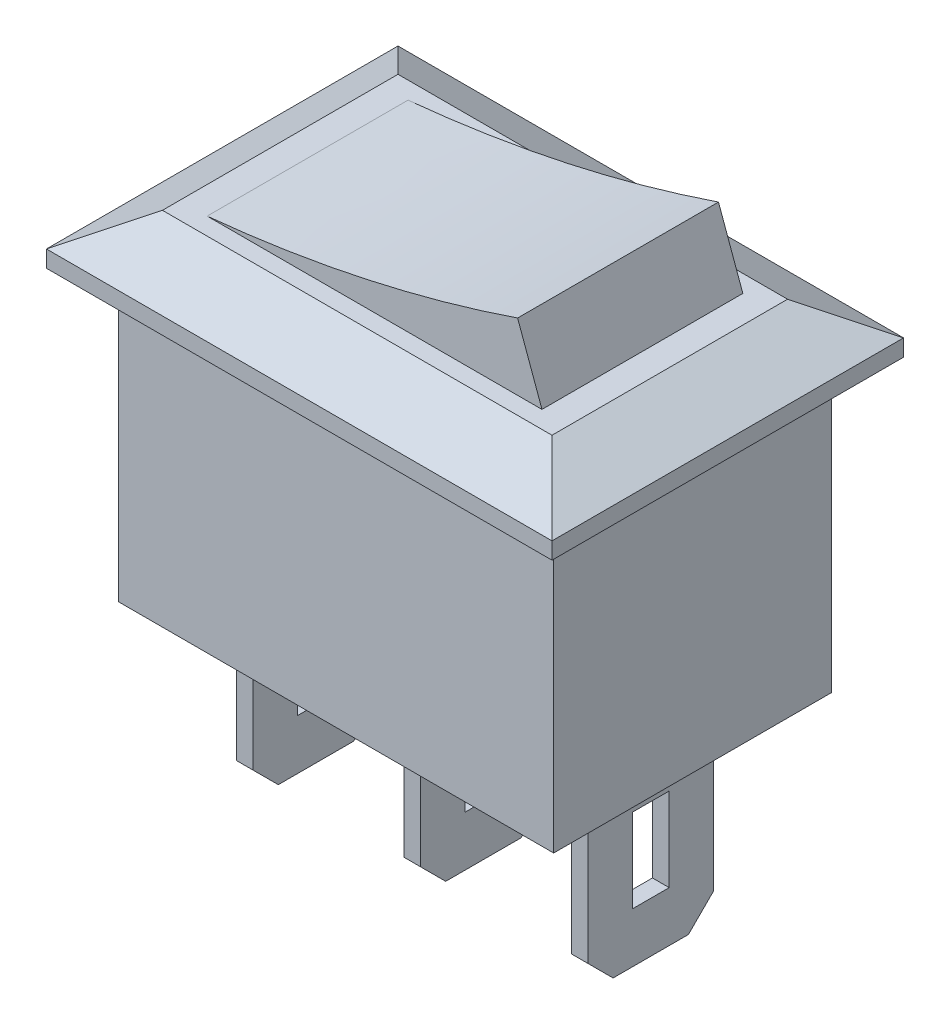
SolidWorks part; units mm, degrees
material "Custom Plastic"
ref_plane "Front Plane" through (0, 0, 0) normal (0, 0, 1) x (1, 0, 0)
ref_plane "Top Plane" through (0, 0, 0) normal (0, 1, 0) x (1, 0, 0)
ref_plane "Right Plane" through (0, 0, 0) normal (1, 0, 0) x (0, 0, -1)
sketch "Sketch1" plane through (0, 0, 0) normal (0, 1, 0) x (1, 0, 0)
  line L1 (6.5, -4.15) -> (-6.5, -4.15)
  line L2 (6.5, -4.15) -> (6.5, 4.15)
  line L3 (6.5, 4.15) -> (-6.5, 4.15)
  line L4 (-6.5, -4.15) -> (-6.5, 4.15)
  line L5 (6.5, -4.15) -> (-6.5, 4.15) construction
  line L6 (6.5, 4.15) -> (-6.5, -4.15) construction
  point P0 (0, 0)
  dimension "D1" = 8.3
  dimension "D2" = 13
extrude "Boss-Extrude1" add sketch "Sketch1" along normal blind 8.65
sketch "Sketch3" plane through (0, 8.65, 0) normal (0, 1, 0) x (1, 0, 0)
  line L1 (7.55, -5.25) -> (-7.55, -5.25)
  line L2 (7.55, -5.25) -> (7.55, 5.25)
  line L3 (7.55, 5.25) -> (-7.55, 5.25)
  line L4 (-7.55, -5.25) -> (-7.55, 5.25)
  line L5 (7.55, -5.25) -> (-7.55, 5.25) construction
  line L6 (7.55, 5.25) -> (-7.55, -5.25) construction
  point P0 (0, 0)
  dimension "D1" = 15.1
  dimension "D2" = 10.5
extrude "Boss-Extrude2" add sketch "Sketch3" along normal blind 1.5
chamfer "Chamfer1" distance 1 angle 60 4 edges at (0, 10.15, -5.25) (7.55, 10.15, 0) (0, 10.15, 5.25) (-7.55, 10.15, 0)
sketch "Sketch4" plane through (0, 10.15, 0) normal (0, 1, 0) x (1, 0, 0)
  line L1 (-5, 3) -> (5, 3)
  line L2 (-5, 3) -> (-5, -3)
  line L3 (-5, -3) -> (5, -3)
  line L4 (5, 3) -> (5, -3)
  line L5 (-5, 3) -> (5, -3) construction
  line L6 (-5, -3) -> (5, 3) construction
  point P0 (0, 0)
  dimension "D1" = 10
  dimension "D2" = 6
extrude "Boss-Extrude3" add sketch "Sketch4" along normal blind 2
sketch "Sketch5" plane through (0, 0, -3) normal (0, 0, -1) x (-1, 0, 0)
  line L0 (-5, 10.15) -> (-4.2721, 12.15)
  line L1 (-5, 12.15) -> (5, 12.15) construction
  line L2 (-5, 10.15) -> (-5, 12.15)
  line L3 (-5, 12.15) -> (5, 12.15)
  line L4 (5, 12.15) -> (5, 10.15)
  line L5 (5, 12.15) -> (5, 10.15) construction
  line L6 (-5, 10.15) -> (5, 10.15) construction
  spline S0 degree 2 poles (-4.2721, 12.15) (0.2515, 10.6096) (5, 10.15) knots 0 0 0 1 1 1
  line M2 (5, 10.15) -> (5, 12.15)
  line M3 (5, 12.15) -> (-5, 12.15)
  line M4 (-5, 12.15) -> (-5, 10.15)
  dimension "D1" = 20
  dimension "D2" = 4.1094
  dimension "D3" = 0.6085
extrude "Cut-Extrude2" cut sketch "Sketch5" against normal up to surface (6 mm away) contours S0 M3 M2 | L0 M4 M3 up to face at (0, 11.15, 3)
sketch "Sketch6" plane through (0, 0, 0) normal (0, -1, 0) x (1, 0, 0)
  line L0 (0, 0) -> (0, -4.15) construction
  line L1 (-0.25, 1.875) -> (0.25, 1.875)
  line L2 (-0.25, 1.875) -> (-0.25, -1.875)
  line L3 (-0.25, -1.875) -> (0.25, -1.875)
  line L4 (0.25, 1.875) -> (0.25, -1.875)
  line L5 (-0.25, 1.875) -> (0.25, -1.875) construction
  line L6 (-0.25, -1.875) -> (0.25, 1.875) construction
  line L7 (6.5, -4.15) -> (-6.5, -4.15) construction
  line L8 (-4.75, -1.875) -> (-5.25, 1.875) construction
  line L9 (4.75, 1.875) -> (5.25, 1.875)
  line L10 (4.75, 1.875) -> (4.75, -1.875)
  line L11 (4.75, -1.875) -> (5.25, -1.875)
  line L12 (5.25, 1.875) -> (5.25, -1.875)
  line L13 (4.75, 1.875) -> (5.25, -1.875) construction
  line L14 (4.75, -1.875) -> (5.25, 1.875) construction
  line L15 (-4.75, 1.875) -> (-5.25, -1.875) construction
  line L16 (-5.25, 1.875) -> (-5.25, -1.875)
  line L17 (-4.75, -1.875) -> (-5.25, -1.875)
  line L18 (-4.75, 1.875) -> (-4.75, -1.875)
  line L19 (-4.75, 1.875) -> (-5.25, 1.875)
  point P0 (0, 0)
  point P10 (5, 0)
  point P19 (-5, 0)
  dimension "D1" = 0.5
  dimension "D2" = 3.75
  dimension "D3" = 4.5
extrude "Boss-Extrude4" add sketch "Sketch6" along normal blind 5.37
chamfer "Chamfer2" distance 0.75 angle 45 6 edges at (-5, -5.37, -1.875) (-5, -5.37, 1.875) (0, -5.37, -1.875) (0, -5.37, 1.875) (5, -5.37, -1.875) (5, -5.37, 1.875)
sketch "Sketch7" plane through (-5.25, 0, 0) normal (-1, 0, 0) x (0, 0, 1)
  line L0 (1.125, -5.37) -> (-1.125, -5.37) construction
  line L1 (0.55, -3.87) -> (-0.55, -3.87)
  line L2 (0.55, -3.87) -> (0.55, -1.37)
  line L3 (0.55, -1.37) -> (-0.55, -1.37)
  line L4 (-0.55, -3.87) -> (-0.55, -1.37)
  point P4 (0, -3.87)
  point P5 (0, -5.37)
  dimension "D1" = 2.5
  dimension "D2" = 1.5
  dimension "D3" = 1.1
extrude "Cut-Extrude3" cut sketch "Sketch7" against normal up to surface (10.5 mm away) up to face at (5.25, -3.33, 0)
